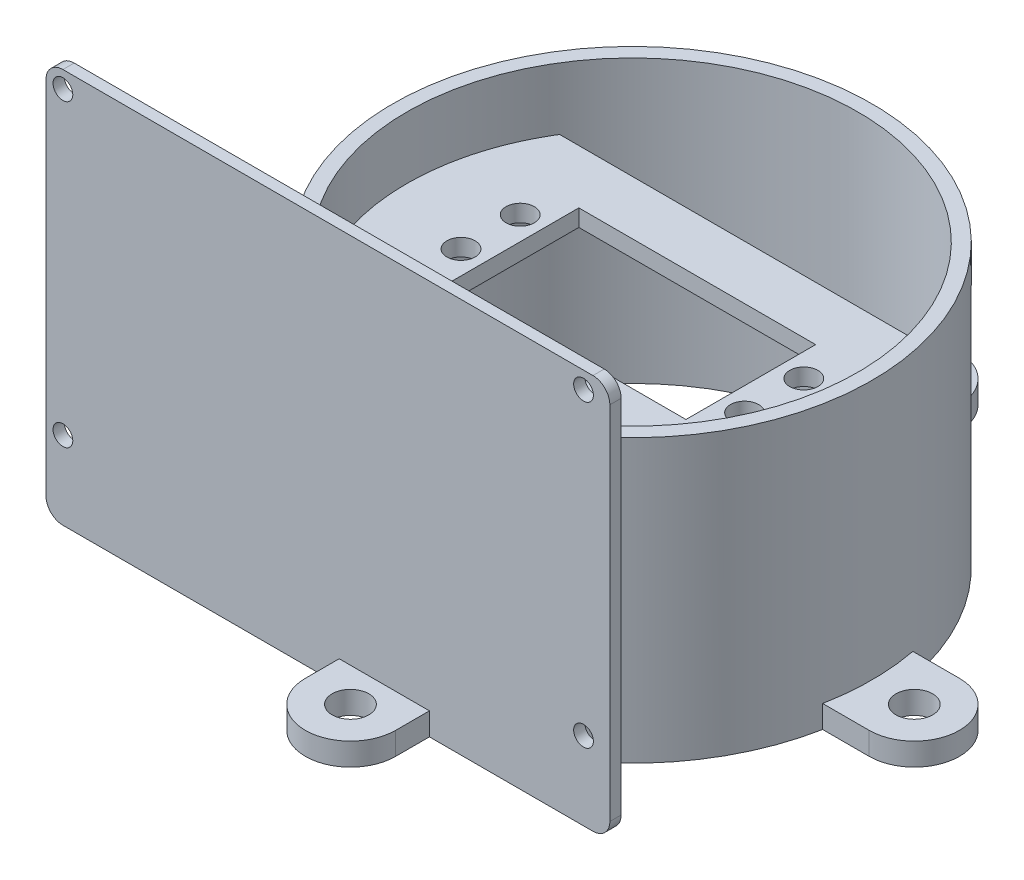
SolidWorks part; units mm, degrees
ref_plane "Front Plane" through (0, 0, 0) normal (0, 0, 1) x (1, 0, 0)
ref_plane "Top Plane" through (0, 0, 0) normal (0, 1, 0) x (1, 0, 0)
ref_plane "Right Plane" through (0, 0, 0) normal (1, 0, 0) x (0, 0, -1)
sketch "Sketch1" plane through (0, 0, 0) normal (0, 1, 0) x (1, 0, 0)
  circle A0 centre (0, 0) radius 40
  circle A1 centre (0, 0) radius 42.5
  dimension "D1" = 80
  dimension "D2" = 85
extrude "Boss-Extrude1" add sketch "Sketch1" along normal blind 50
sketch "Sketch2" plane through (0, 0, 0) normal (0, -1, 0) x (1, 0, 0)
  line L0 (42.5, 0) -> (50.0003, 0) construction
  line L1 (41.7403, 8) -> (50.0003, 8)
  line L2 (41.7403, -8) -> (50.0003, -8)
  circle A0 centre (0, 0) radius 42.5 construction
  circle A1 centre (50.0003, 0) radius 3.25
  arc A2 (50.0003, -8) -> (50.0003, 8) centre (50.0003, 0) ccw
  dimension "D2" = 6.5
  dimension "D4" = 16
  dimension "D1" = 8.26
  dimension "D3" = 8
extrude "Boss-Extrude2" add sketch "Sketch2" against normal blind 4
pattern_circular "CirPattern1" count 4 over 360 about axis through (0, 0, 0) along (0, 1, 0) of "Boss-Extrude2"
ref_plane "Plane1" through (0, 36, 0) normal (0, 1, 0) x (1, 0, 0)
sketch "Sketch4" plane through (0, 36, 0) normal (0, 1, 0) x (1, 0, 0)
  line L5 (34, -21.0713) -> (-34, -21.0713)
  line L7 (34, 21.0713) -> (-34, 21.0713)
  line L9 (34, -21.0713) -> (-34, 21.0713) construction
  line L10 (34, 21.0713) -> (-34, -21.0713) construction
  circle A3 centre (0, 0) radius 40 construction
  arc A4 (-34, 21.0713) -> (-34, -21.0713) centre (0, 0) ccw
  arc A5 (34, -21.0713) -> (34, 21.0713) centre (0, 0) ccw
  point P0 (0, 0)
  dimension "D1" = 68
extrude "Boss-Extrude3" add sketch "Sketch4" along normal blind 3 separate body
sketch "Sketch3" plane through (0, 39, 0) normal (0, 1, 0) x (1, 0, 0)
  line L0 (-25.15, 5.25) -> (25.15, 5.25) construction
  line L1 (-25.15, 5.25) -> (-25.15, -5.25) construction
  line L2 (-25.15, -5.25) -> (25.15, -5.25) construction
  line L3 (25.15, 5.25) -> (25.15, -5.25) construction
  line L4 (-25.15, 5.25) -> (25.15, -5.25) construction
  line L5 (25.15, -5.25) -> (25.15, 5.25) construction
  line L6 (25.15, 5.25) -> (-25.15, -5.25) construction
  line L7 (21, -11.5) -> (-21, -11.5)
  line L8 (21, -11.5) -> (21, 11.5)
  line L9 (21, 11.5) -> (-21, 11.5)
  line L10 (-21, -11.5) -> (-21, 11.5)
  line L11 (21, -11.5) -> (-21, 11.5) construction
  line L12 (21, 11.5) -> (-21, -11.5) construction
  circle A0 centre (25.15, 5.25) radius 2.5
  circle A1 centre (25.15, -5.25) radius 2.5
  circle A2 centre (-25.15, -5.25) radius 2.5
  circle A3 centre (-25.15, 5.25) radius 2.5
  circle A4 centre (0, 0) radius 12.5 construction
  dimension "D1" = 5
  dimension "D4" = 25
  dimension "D2" = 10.5
  dimension "D3" = 50.3
  dimension "D5" = 42
  dimension "D6" = 23
extrude "Cut-Extrude1" cut sketch "Sketch3" against normal up to next (3 mm away)
sketch "Sketch5" plane through (0, 0, 0) normal (0, 0, 1) x (1, 0, 0)
  line L0 (0, 0) -> (0, 36) construction
  line L1 (-60, 70) -> (40, 70)
  line L2 (-60, 70) -> (-60, 0)
  line L3 (-60, 0) -> (40, 0)
  line L4 (40, 70) -> (40, 0)
  line L5 (46.75, 36) -> (-46.75, 36) construction
  line L6 (-10, 0) -> (-10, 70) construction
  circle A0 centre (-57, 67) radius 1.75
  circle A1 centre (35.33, 67) radius 1.75
  circle A2 centre (-57, 13.85) radius 1.75
  circle A3 centre (35.33, 13.85) radius 1.75
  dimension "D3" = 3.5
  dimension "D4" = 92.33
  dimension "D5" = 3
  dimension "D6" = 3
  dimension "D8" = 53.15
  dimension "D1" = 100
  dimension "D2" = 70
  dimension "D9" = 10
  dimension "D7" = 2
extrude "Boss-Extrude4" add sketch "Sketch5" along normal blind 2 from offset 42
fillet "Fillet1" radius 3 4 edges at (40, 70, 43) (-60, 70, 43) (40, 0, 43) (-60, 0, 43)
